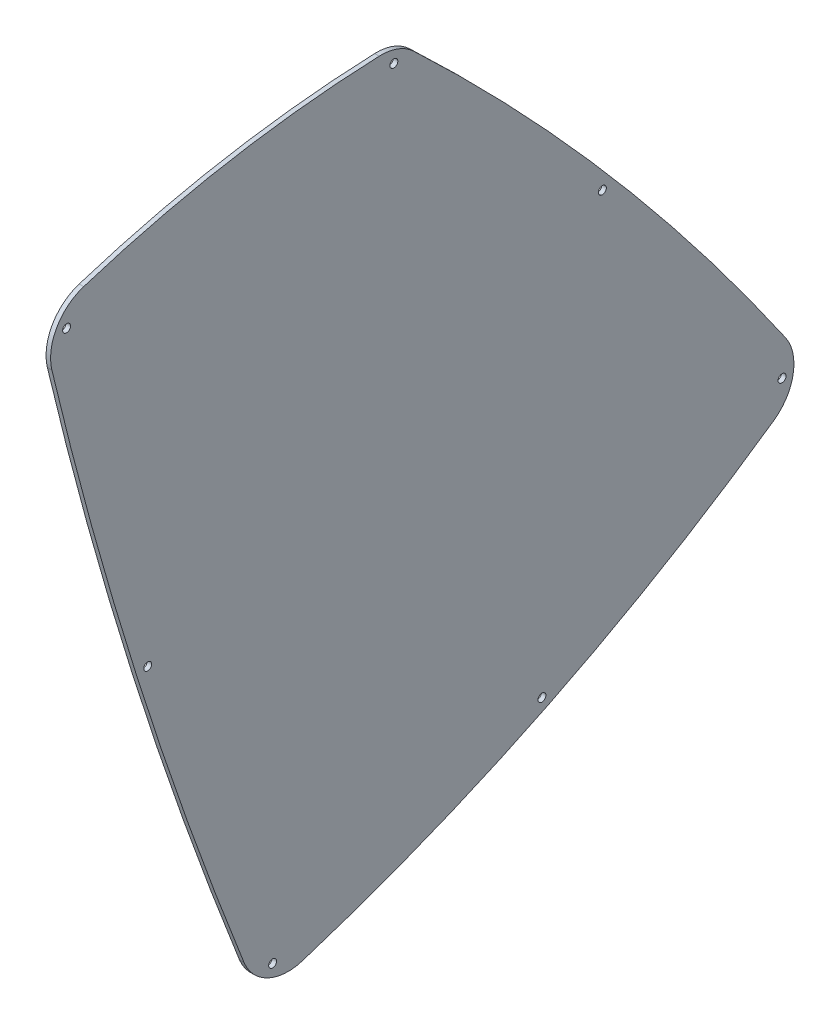
SolidWorks part; units mm, degrees
material "metacrilato"
ref_plane "Alzado" through (0, 0, 0) normal (0, 0, 1) x (1, 0, 0)
ref_plane "Planta" through (0, 0, 0) normal (0, 1, 0) x (1, 0, 0)
ref_plane "Vista lateral" through (0, 0, 0) normal (1, 0, 0) x (0, 0, -1)
sketch "Croquis2" plane through (0, 0, 0) normal (1, 0, 0) x (0, 0, -1)
  arc A0 (-1606.6341, 136.1126) -> (-1613.3234, 124.2738) centre (-1603.5943, 126.5858) ccw construction
  circle A1 centre (-1617.5244, 134.4568) radius 1.25 construction
  arc A2 (-1479.1065, 158.4751) -> (-1606.6341, 136.1126) centre (-1460.7228, -321.1727) ccw construction
  circle A3 centre (-1581.7176, -12.7056) radius 1 construction
  circle A4 centre (-1581.7176, -12.7056) radius 1 construction
  circle A5 centre (-1581.7176, -12.7056) radius 1.75
  circle A6 centre (-1526.588, -153.7876) radius 1.25 construction
  circle A7 centre (-1526.588, -153.7876) radius 1.25 construction
  arc A8 (-1471.8478, 155.7435) -> (-1479.1065, 158.4751) centre (-1478.7235, 148.4824) ccw construction
  circle A9 centre (-1526.588, -153.7876) radius 1.75
  arc A16 (-1309.2619, -34.0531) -> (-1471.8478, 155.7435) centre (-2296.9385, -715.5918) ccw construction
  arc A17 (-1311.7591, -47.9257) -> (-1309.2619, -34.0531) centre (-1317.4926, -39.7326) ccw construction
  arc A18 (-1516.7127, -148.8789) -> (-1311.7591, -47.9257) centre (-1741.7721, 566.5568) ccw construction
  arc A19 (-1529.0083, -143.0284) -> (-1516.7127, -148.8789) centre (-1519.7135, -139.3397) ccw construction
  arc A20 (-1613.3234, 124.2738) -> (-1529.0083, -143.0284) centre (275.6718, 573.1702) ccw construction
  arc A21 (-1606.6341, 136.1126) -> (-1613.3234, 124.2738) centre (-1603.5943, 126.5858) ccw construction
  arc A22 (-1479.1065, 158.4751) -> (-1606.6341, 136.1126) centre (-1460.7228, -321.1727) ccw construction
  arc A23 (-1471.8478, 155.7435) -> (-1479.1065, 158.4751) centre (-1478.7235, 148.4824) ccw construction
  arc A24 (-1309.2619, -34.0531) -> (-1471.8478, 155.7435) centre (-2296.9385, -715.5918) ccw construction
  arc A25 (-1311.7591, -47.9257) -> (-1309.2619, -34.0531) centre (-1317.4926, -39.7326) ccw construction
  arc A26 (-1516.7127, -148.8789) -> (-1311.7591, -47.9257) centre (-1741.7721, 566.5568) ccw construction
  arc A27 (-1529.0083, -143.0284) -> (-1516.7127, -148.8789) centre (-1519.7135, -139.3397) ccw construction
  arc A28 (-1613.3234, 124.2738) -> (-1529.0083, -143.0284) centre (275.6718, 573.1702) ccw construction
  arc A29 (-1624.0253, 121.7307) -> (-1539.2326, -147.086) centre (275.6718, 573.1702) ccw
  arc A30 (-1539.2326, -147.086) -> (-1513.4118, -159.3719) centre (-1519.7135, -139.3397) ccw
  arc A31 (-1513.4118, -159.3719) -> (-1305.4522, -56.9381) centre (-1741.7721, 566.5568) ccw
  arc A34 (-1305.4522, -56.9381) -> (-1300.2082, -27.8057) centre (-1317.4926, -39.7326) ccw
  arc A35 (-1300.2082, -27.8057) -> (-1464.2845, 163.7308) centre (-2296.9385, -715.5918) ccw
  arc A36 (-1464.2845, 163.7308) -> (-1479.5278, 169.467) centre (-1478.7235, 148.4824) ccw
  arc A37 (-1479.5278, 169.467) -> (-1609.9779, 146.5921) centre (-1460.7228, -321.1727) ccw
  arc A38 (-1609.9779, 146.5921) -> (-1624.0253, 121.7307) centre (-1603.5943, 126.5858) ccw
  circle A50 centre (-1617.5244, 134.4568) radius 1.25 construction
  circle A51 centre (-1617.5244, 134.4568) radius 1.75
  circle A52 centre (-1407.718, -111.6348) radius 1.5 construction
  circle A53 centre (-1407.718, -111.6348) radius 1.5 construction
  circle A54 centre (-1407.718, -111.6348) radius 1.75
  circle A55 centre (-1473.0884, 163.4572) radius 1.5 construction
  circle A56 centre (-1381.0438, 68.9927) radius 1.5 construction
  circle A57 centre (-1301.7457, -42.5671) radius 1.5 construction
  circle A58 centre (-1473.0884, 163.4572) radius 1.5 construction
  circle A59 centre (-1381.0438, 68.9927) radius 1.5 construction
  circle A60 centre (-1301.7457, -42.5671) radius 1.5 construction
  circle A61 centre (-1301.7457, -42.5671) radius 1.75
  circle A62 centre (-1381.0438, 68.9927) radius 1.75
  circle A63 centre (-1473.0884, 163.4572) radius 1.75
  dimension "D3" = 3.5
  dimension "D1" = 11
extrude "Saliente-Extruir1" add sketch "Croquis2" along normal blind 2
